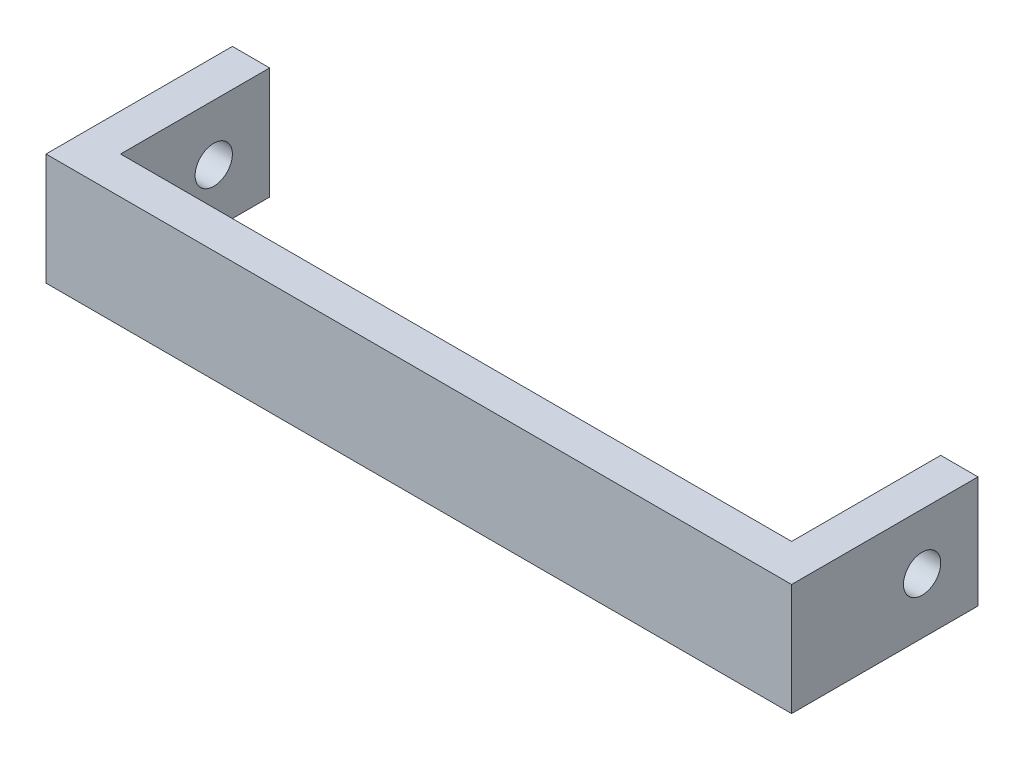
SolidWorks part; units mm, degrees
ref_plane "Front Plane" through (0, 0, 0) normal (0, 0, 1) x (1, 0, 0)
ref_plane "Top Plane" through (0, 0, 0) normal (0, 1, 0) x (1, 0, 0)
ref_plane "Right Plane" through (0, 0, 0) normal (1, 0, 0) x (0, 0, -1)
sketch "Sketch1" plane through (0, 0, 0) normal (0, 1, 0) x (1, 0, 0)
  line L1 (-50, 2.5) -> (50, 2.5)
  line L2 (-50, 2.5) -> (-50, -2.5)
  line L3 (-50, -2.5) -> (50, -2.5)
  line L4 (50, 2.5) -> (50, -2.5)
  line L5 (-50, 2.5) -> (50, -2.5) construction
  line L6 (-50, -2.5) -> (50, 2.5) construction
  line L7 (-50, 2.5) -> (-45, 2.5)
  line L8 (-50, 2.5) -> (-50, 22.5)
  line L9 (-50, 22.5) -> (-45, 22.5)
  line L10 (-45, 2.5) -> (-45, 22.5)
  line L11 (50, 2.5) -> (45, 2.5)
  line L12 (50, 2.5) -> (50, 22.5)
  line L13 (50, 22.5) -> (45, 22.5)
  line L14 (45, 2.5) -> (45, 22.5)
  point P0 (0, 0)
  dimension "D1" = 100
  dimension "D2" = 5
  dimension "D3" = 5
  dimension "D4" = 5
  dimension "D5" = 20
  dimension "D6" = 20
extrude "Boss-Extrude1" add sketch "Sketch1" along normal blind 15 contours L4 L1 L2 L3 | L1 L10 L9 L8 | L14 L1 L12 L13
sketch "Sketch2" plane through (-50, 0, 0) normal (-1, 0, 0) x (0, 0, 1)
  line L0 (-22.5, 15) -> (-22.5, 0) construction
  line L3 (-22.5, 15) -> (2.5, 15) construction
  circle A0 centre (-15, 7.5) radius 2.5
  dimension "D1" = 5
  dimension "D2" = 7.5
  dimension "D3" = 7.5
extrude "Cut-Extrude1" cut sketch "Sketch2" against normal through all
